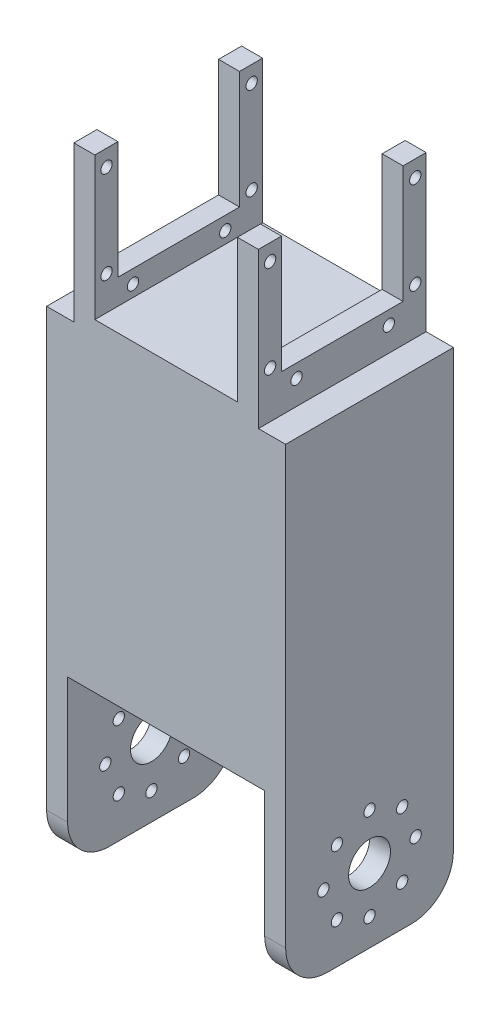
SolidWorks part; units mm, degrees
other "Markup1"
sketch "Sketch10" plane through (-11.5, 37, 0) normal (-0.0875, 0.3291, 0.9402) x (0.9883, -0.0896, 0.1234)
material "Aluminium 1050"
ref_plane "Front Plane" through (0, 0, 0) normal (0, 0, 1) x (1, 0, 0)
ref_plane "Top Plane" through (0, 0, 0) normal (0, 1, 0) x (1, 0, 0)
ref_plane "Right Plane" through (0, 0, 0) normal (1, 0, 0) x (0, 0, -1)
sketch "Sketch2" plane through (0, 0, 0) normal (0, 1, 0) x (1, 0, 0)
  line L0 (0, 0) -> (34, 0)
  line L1 (34, 0) -> (34, 40)
  line L2 (34, 40) -> (0, 40)
  line L3 (0, 40) -> (0, 0)
  dimension "D1" = 34
  dimension "D2" = 40
extrude "Boss-Extrude1" add sketch "Sketch2" along normal blind 3
sketch "Sketch3" plane through (0, 0, 0) normal (0, 1, 0) x (1, 0, 0)
  line L0 (0, 0) -> (-5, 0)
  line L1 (-5, 0) -> (-5, 40)
  line L2 (-5, 40) -> (0, 40)
  line L3 (0, 40) -> (0, 0)
  line L4 (17, 40) -> (17, 0) construction
  line L5 (34, 40) -> (0, 40) construction
  line L6 (0, 0) -> (34, 0) construction
  line L7 (34, 40) -> (34, 0)
  line L8 (39, 40) -> (34, 40)
  line L9 (39, 0) -> (39, 40)
  line L10 (34, 0) -> (39, 0)
  dimension "D1" = 5
extrude "Boss-Extrude2" add sketch "Sketch3" along normal blind 37
sketch "Sketch4" plane through (-5, 0, 0) normal (-1, 0, 0) x (0, 0, 1)
  line L0 (-20, 37) -> (-20, 0) construction
  line L1 (-40, 37) -> (0, 37) construction
  line L2 (-40, 0) -> (0, 0) construction
  line L4 (-34.5, 9) -> (-5.5, 9)
  line L11 (-34.5, 37) -> (-34.5, 9)
  line L12 (-5.5, 37) -> (-5.5, 9)
  line L13 (-34.5, 37) -> (-5.5, 37)
  line L14 (-34.5, 37) -> (-34.5, 0) construction
  line L15 (-5.5, 37) -> (-5.5, 0) construction
  circle A2 centre (-2.8, 33.1) radius 1.35
  circle A3 centre (-2.8, 11.1) radius 1.35
  circle A4 centre (-9.1, 5.8) radius 1.35
  circle A5 centre (-37.4, 11.1) radius 1.35
  circle A6 centre (-31.1, 5.8) radius 1.35
  circle A7 centre (-37.4, 33.1) radius 1.35
  dimension "D1" = 2.7
  dimension "D2" = 2.7
  dimension "D3" = 2.7
  dimension "D4" = 2.7
  dimension "D5" = 2.7
  dimension "D6" = 2.7
  dimension "D7" = 14.5
  dimension "D8" = 14.5
  dimension "D9" = 28
extrude "Cut-Extrude1" cut sketch "Sketch4" against normal up to surface (44 mm away) up to face at (39, 18.5, -20)
sketch "Sketch5" plane through (0, 0, 0) normal (0, -1, 0) x (-1, 0, 0)
  line L0 (-17, 0) -> (-17, 40) construction
  line L1 (5, 0) -> (-39, 0) construction
  line L2 (-39, 40) -> (5, 40) construction
  line L3 (11.5, 0) -> (-45.5, 0)
  line L4 (-45.5, 0) -> (-45.5, 40)
  line L5 (-45.5, 40) -> (11.5, 40)
  line L6 (11.5, 0) -> (11.5, 40)
  dimension "D1" = 28.5
extrude "Boss-Extrude3" add sketch "Sketch5" along normal blind 3 contours L5 L6 L3 L4
sketch "Sketch6" plane through (0, -3, 0) normal (0, -1, 0) x (1, 0, 0)
  line L0 (-11.5, 0) -> (45.5, 0)
  line L1 (45.5, 0) -> (45.5, -40)
  line L2 (45.5, -40) -> (-11.5, -40)
  line L3 (-11.5, -40) -> (-11.5, 0)
  line L4 (-8.5, -37) -> (-8.5, -3)
  line L5 (-8.5, -3) -> (42.5, -3)
  line L6 (42.5, -3) -> (42.5, -37)
  line L7 (42.5, -37) -> (-8.5, -37)
  dimension "D1" = 3
extrude "Boss-Extrude4" add sketch "Sketch6" along normal blind 68.03
sketch "Sketch7" plane through (0, -71.03, 0) normal (0, -1, 0) x (1, 0, 0)
  line L0 (-11.5, 0) -> (45.5, 0)
  line L1 (45.5, 0) -> (45.5, -40)
  line L2 (45.5, -40) -> (-11.5, -40)
  line L3 (-11.5, -40) -> (-11.5, 0)
extrude "Boss-Extrude5" add sketch "Sketch7" along normal blind 3
sketch "Sketch8" plane through (0, -74.03, 0) normal (0, -1, 0) x (1, 0, 0)
  line L0 (17, 0) -> (17, -40) construction
  line L1 (45.5, 0) -> (-11.5, 0) construction
  line L2 (-11.5, -40) -> (45.5, -40) construction
  line L3 (-6.5, 0) -> (-6.5, -40)
  line L4 (40.5, 0) -> (40.5, -40)
  line L5 (-6.5, 0) -> (-11.5, 0)
  line L6 (-11.5, 0) -> (-11.5, -40)
  line L7 (-11.5, -40) -> (-6.5, -40)
  line L8 (40.5, 0) -> (45.5, 0)
  line L9 (45.5, 0) -> (45.5, -40)
  line L10 (45.5, -40) -> (40.5, -40)
  dimension "D1" = 23.5
  dimension "D2" = 23.5
extrude "Boss-Extrude6" add sketch "Sketch8" along normal blind 40
sketch "Sketch9" plane through (45.5, 0, 0) normal (1, 0, 0) x (0, 0, -1)
  line L0 (0, -104.03) -> (0, -74.03)
  line L1 (0, -74.03) -> (40, -74.03)
  line L2 (40, -74.03) -> (40, -104.03)
  line L3 (30, -114.03) -> (10, -114.03)
  line L4 (0, -96.53) -> (40, -96.53) construction
  line L5 (0, -104.03) -> (0, -114.03)
  line L6 (0, -114.03) -> (10, -114.03)
  line L7 (30, -114.03) -> (40, -114.03)
  line L8 (40, -114.03) -> (40, -104.03)
  arc A0 (30, -114.03) -> (40, -104.03) centre (30, -104.03) ccw
  arc A1 (0, -104.03) -> (10, -114.03) centre (10, -104.03) ccw
  circle A2 centre (20, -96.53) radius 5
  circle A3 centre (20, -96.53) radius 11 construction
  circle A4 centre (20, -85.53) radius 1.35
  circle A5 centre (27.7782, -88.7518) radius 1.35
  circle A6 centre (20, -96.53) radius 11 construction
  circle A7 centre (31, -96.53) radius 1.35
  circle A8 centre (20, -96.53) radius 11 construction
  circle A9 centre (27.7782, -104.3082) radius 1.35
  circle A10 centre (20, -96.53) radius 11 construction
  circle A11 centre (20, -107.53) radius 1.35
  circle A12 centre (20, -96.53) radius 11 construction
  circle A13 centre (12.2218, -104.3082) radius 1.35
  circle A14 centre (20, -96.53) radius 11 construction
  circle A15 centre (9, -96.53) radius 1.35
  circle A16 centre (20, -96.53) radius 11 construction
  circle A17 centre (12.2218, -88.7518) radius 1.35
  circle A18 centre (20, -96.53) radius 11 construction
  point P10 (40, -114.03)
  point P13 (0, -114.03)
  point P45 (20, -96.53)
  line M12 (0, 0) -> (0, -114.03)
  line M13 (0, -114.03) -> (40, -114.03)
  line M14 (40, -114.03) -> (40, 0)
  dimension "D1" = 10
  dimension "D3" = 10
  dimension "D4" = 22
  dimension "D5" = 2.7
  dimension "D2" = 22.5
  dimension "D6" = 8
extrude "Cut-Extrude2" cut sketch "Sketch9" against normal up to surface (57 mm away) contours A0 M13 M14 | A1 M12 M13 | A2 | A9 | A11 | A13 | A7 | A5 | A4 | A17 | A15 up to face at (-11.5, -57.015, -20)
